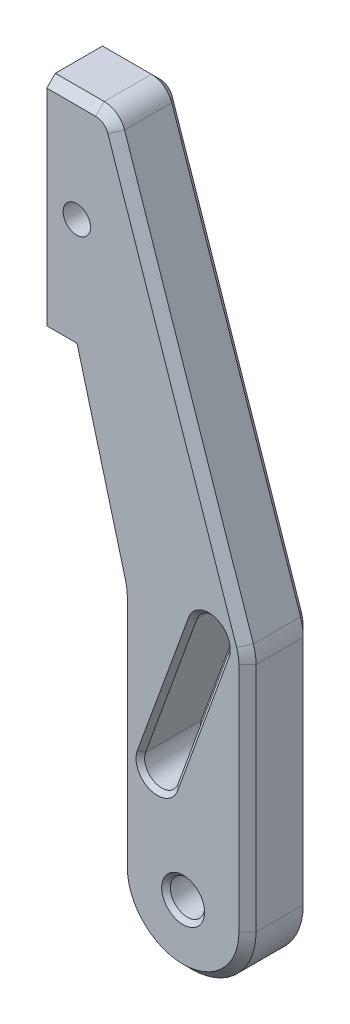
SolidWorks part; units mm, degrees
ref_plane "Alzado" through (0, 0, 0) normal (0, 0, 1) x (1, 0, 0)
ref_plane "Planta" through (0, 0, 0) normal (0, 1, 0) x (1, 0, 0)
ref_plane "Vista lateral" through (0, 0, 0) normal (1, 0, 0) x (0, 0, -1)
sketch "Croquis1" plane through (0, 0, 0) normal (0, 0, 1) x (1, 0, 0)
  line L0 (-15, 0) -> (-15, 55.9808)
  line L1 (-15, 55.9808) -> (-26.7949, 100)
  line L2 (-31.7949, 150) -> (-16.7949, 150)
  line L3 (-16.7949, 150) -> (15, 55.9808)
  line L4 (15, 55.9808) -> (15, 0)
  line L5 (-15, 55.9808) -> (-26.6921, 55.9808) construction
  line L6 (5.9854, 55.9808) -> (-5.9854, 23.0915) construction
  line L7 (9.7441, 54.6127) -> (-2.2266, 21.7234)
  line L8 (2.2266, 57.3488) -> (-9.7441, 24.4596)
  line L9 (-15, 55.9808) -> (15, 55.9808) construction
  line L10 (-31.7949, 150) -> (-31.7949, 100)
  line L11 (-31.7949, 100) -> (-26.7949, 100)
  arc A0 (-15, 0) -> (15, 0) centre (0, 0) ccw
  circle A1 centre (0, 0) radius 4
  arc A2 (9.7441, 54.6127) -> (2.2266, 57.3488) centre (5.9854, 55.9808) ccw
  arc A3 (-9.7441, 24.4596) -> (-2.2266, 21.7234) centre (-5.9854, 23.0915) ccw
  point P12 (0, 39.5361)
  point P18 (0, 55.9808)
  dimension "D1" = 30
  dimension "D5" = 8
  dimension "D8" = 50
  dimension "D2" = 75
  dimension "D3" = 15
  dimension "D4" = 150
  dimension "D6" = 8
  dimension "D7" = 35
  dimension "D9" = 5
  dimension "D10" = 70
extrude "Saliente-Extruir1" add sketch "Croquis1" along normal mid plane 15
sketch "Croquis2" plane through (0, 0, 7.5) normal (0, 0, 1) x (1, 0, 0)
  line L0 (-31.7949, 150) -> (-31.7949, 100) construction
  circle A0 centre (-24.7949, 125) radius 3.19
  point P5 (-31.7949, 125)
  dimension "D1" = 6.38
  dimension "D2" = 7
extrude "Cortar-Extruir1" cut sketch "Croquis2" against normal through all
fillet "Redondeo1" radius 12 2 edges at (-15, 55.9808, 0) (15, 55.9808, 0)
chamfer "Chaflán1" distance 1 angle 45 2 edges at (4, 0, -7.5) (4, 0, 7.5)
fillet "Redondeo2" radius 5 1 edges at (-16.7949, 150, 0)
chamfer "Chaflán2" distance 2 angle 45 18 edges at (-26.0886, 150, -7.5) (-17.4675, 149.0626, -7.5) (-0.6391, 102.2263, -7.5) (14.8408, 55.9546, -7.5) (15, 27.0033, -7.5) (0, -15, -7.5) (-15, 27.2005, -7.5) (-15.1027, 55.9672, -7.5) (-21.1019, 78.7534, -7.5) (-26.0886, 150, 7.5) (-17.4675, 149.0626, 7.5) (-0.6391, 102.2263, 7.5) (14.8408, 55.9546, 7.5) (15, 27.0033, 7.5) (0, -15, 7.5) (-15, 27.2005, 7.5) (-15.1027, 55.9672, 7.5) (-21.1019, 78.7534, 7.5)
chamfer "Chaflán3" distance 1 angle 45 8 edges at (-3.7588, 40.9042, 7.5) (-7.3534, 19.3327, 7.5) (7.3534, 59.7395, 7.5) (3.7588, 38.1681, 7.5) (-3.7588, 40.9042, -7.5) (-7.3534, 19.3327, -7.5) (7.3534, 59.7395, -7.5) (3.7588, 38.1681, -7.5)
